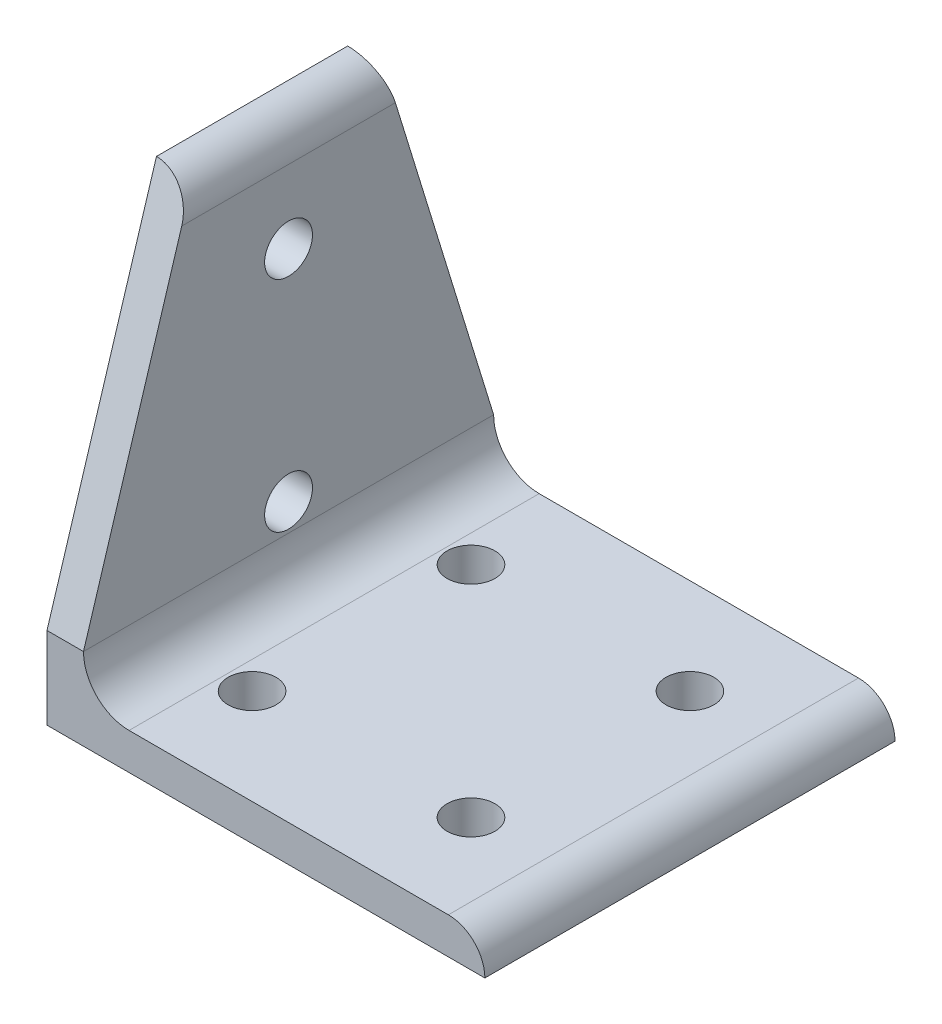
SolidWorks part; units mm, degrees
ref_plane "Front Plane" through (0, 0, 0) normal (0, 0, 1) x (1, 0, 0)
ref_plane "Top Plane" through (0, 0, 0) normal (0, 1, 0) x (1, 0, 0)
ref_plane "Right Plane" through (0, 0, 0) normal (1, 0, 0) x (0, 0, -1)
sketch "Sketch1" plane through (0, 0, 0) normal (0, 0, 1) x (1, 0, 0)
  line L0 (38.1, -38.1) -> (-38.1, -38.1) construction
  line L1 (-38.1, 38.1) -> (-38.1, -38.1) construction
  line L2 (38.1, -38.1) -> (38.1, -31.75) construction
  point P3 (0, -38.1)
  point P6 (-38.1, 0)
  dimension "Length" = 76.2
  dimension "Thickness" = 6.35
sketch "Sketch2" plane through (0, 0, 0) normal (1, 0, 0) x (0, 0, -1)
  line L0 (35.687, 0) -> (-35.687, 0) construction
  line L1 (-16.637, 38.1) -> (16.637, 38.1) construction
  line L3 (-4.1656, 19.05) -> (4.1656, 19.05) construction
  line L5 (0, 38.1) -> (0, -38.1) construction
  point P4 (0, 0)
  point P10 (0, 19.05)
  point P13 (0, 38.1)
  point P20 (0, 38.1)
sketch "Sketch3" plane through (0, 0, 0) normal (0, 1, 0) x (1, 0, 0)
  line L0 (38.1, 0) -> (-38.1, 0) construction
  line L1 (38.1, 0) -> (-38.1, 0) construction
  point P2 (-19.05, 19.05)
  dimension "D1" = 38.1
sketch "Sketch4" plane through (0, 0, 0) normal (0, 0, 1) x (1, 0, 0)
  line L0 (-38.1, 38.1) -> (-38.1, -38.1)
  line L1 (-38.1, -38.1) -> (38.1, -38.1)
  line L2 (-31.75, 31.75) -> (-31.75, -23.8252)
  line L3 (-23.8252, -31.75) -> (31.75, -31.75)
  arc A0 (-31.75, -23.8252) -> (-23.8252, -31.75) centre (-23.8252, -23.8252) ccw
  arc A1 (31.75, -31.75) -> (38.1, -38.1) centre (31.75, -38.1) cw
  arc A2 (-31.75, 31.75) -> (-38.1, 38.1) centre (-38.1, 31.75) ccw
  dimension "Radius" = 7.9248
extrude "Boss-Extrude1" add sketch "Sketch4" against normal up to vertex (35.687 mm away) and the other way up to vertex (35.687 mm away) up to point (0, 0, -35.687) other way up to point (0, 0, 35.687)
sketch "Sketch5" plane through (-31.75, 0, 0) normal (1, 0, 0) x (0, 0, -1)
  line L0 (-35.687, -23.8252) -> (-16.637, 38.1)
  line L1 (35.687, 38.1) -> (-35.687, 38.1) construction
  line L3 (0, 38.1) -> (0, -38.1) construction
  line L4 (0, 38.1) -> (0, -38.1) construction
  line L6 (-35.687, -23.8252) -> (-35.687, 38.1)
  line L7 (-35.687, 38.1) -> (-16.637, 38.1)
  line L11 (35.687, 38.1) -> (16.637, 38.1)
  line L12 (35.687, -23.8252) -> (35.687, 38.1)
  line L13 (35.687, -23.8252) -> (16.637, 38.1)
extrude "Cut-Extrude1" cut sketch "Sketch5" against normal through all both and the other way through all
sketch "Sketch6" plane through (-31.75, 0, 0) normal (1, 0, 0) x (0, 0, -1)
  line L0 (-4.1656, 19.05) -> (4.1656, 19.05) construction
  line L1 (35.687, 0) -> (-35.687, 0) construction
  line L2 (35.687, 0) -> (-35.687, 0) construction
  circle A0 centre (0, 19.05) radius 4.1656
  circle A1 centre (0, -19.05) radius 4.1656
extrude "Cut-Extrude2" cut sketch "Sketch6" against normal through all both and the other way through all
sketch "Sketch7" plane through (0, -31.75, 0) normal (0, 1, 0) x (1, 0, 0)
  line L0 (38.1, 0) -> (-38.1, 0) construction
  line L1 (0, 35.687) -> (0, -35.687) construction
  line L2 (38.1, 0) -> (-38.1, 0) construction
  line L3 (0, 35.687) -> (0, -35.687) construction
  circle A0 centre (-19.05, 19.05) radius 4.1656
  circle A1 centre (19.05, 19.05) radius 4.1656
  circle A2 centre (19.05, -19.05) radius 4.1656
  circle A3 centre (-19.05, -19.05) radius 4.1656
  dimension "D1" = 8.3312
extrude "Cut-Extrude3" cut sketch "Sketch7" against normal through all
equation "\"D1@Sketch3\" = \"Hole Spacing@Sketch2\""
equation "\"D1@Sketch7\"=\"Hole Dia@Sketch2\""
